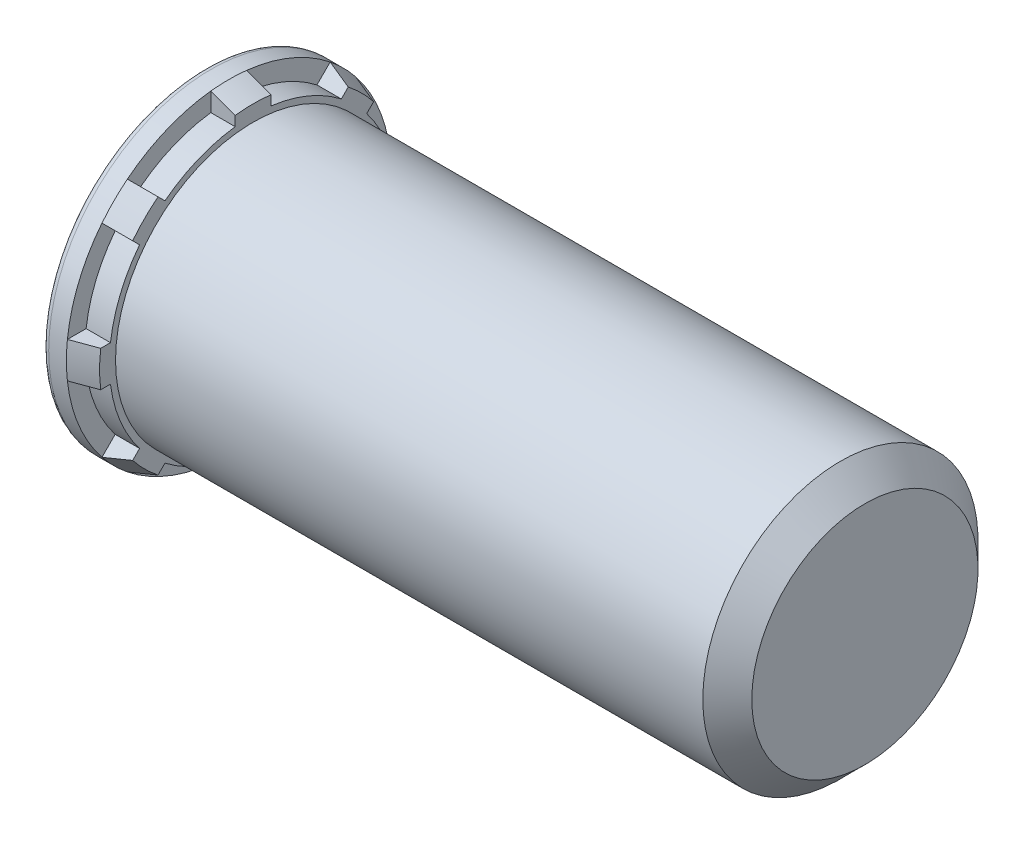
SolidWorks part; units mm, degrees
revolve "BaseBody" add sketch "BodySke" angle 360 about L6
sketch "BodySke" plane through (0, 0, 0) normal (0, 0, 1) x (1, 0, 0)
  line L0 (-0.4425, 2.8295) -> (-0.4425, 0)
  line L1 (0.4425, 2.7889) -> (0.4425, 2.5)
  line L2 (0, 2.95) -> (0.4425, 2.7889)
  line L3 (0.4425, 2.5) -> (11.1125, 2.5)
  line L4 (11.5575, 2.055) -> (11.5575, 0)
  line L5 (11.5575, 0) -> (-0.4425, 0)
  line L6 (0, 0) -> (50.554, 0) construction
  line L7 (-0.4425, 2.8295) -> (-0.44, 2.8295)
  line L8 (11.5575, 2.055) -> (11.1125, 2.5)
  line L9 (-0.322, 2.95) -> (0, 2.95)
  line L11 (0.8, 19.05) -> (0.8, -3.175) construction
  line L13 (-0.44, 2.8295) -> (-0.44, 2.832)
  arc A0 (-0.44, 2.832) -> (-0.322, 2.95) centre (-0.322, 2.832) cw
  dimension "Fillet_rad" = 0.118
  dimension "Body_ch_ang" = 45
  dimension "Minor_dia" = 4.11
  dimension "Diameter" = 5
  dimension "H_dia" = 5.9
  dimension "Advance" = 0.8
  dimension "D1" = 20
  dimension "Length" = 12
  dimension "D2" = 0.0025
  dimension "D3" = 0.0025
  dimension "Clinch_ht" = 0.4425
  dimension "Head_ht" = 0.885
cosmetic thread "ThreadCosmetic" [suppressed] parameters "Thread_length"=9.3, "Thread_minor"=4.11
ref_plane "Plane1" through (0, 0, 0) normal (0, 0, 1) x (1, 0, 0)
ref_plane "Plane2" through (0, 0, 0) normal (0, 1, 0) x (1, 0, 0)
ref_plane "Plane3" through (0, 0, 0) normal (1, 0, 0) x (0, 0, -1)
sketch "ThdSchSke" plane through (0, 0, 0) normal (0, 0, 1) x (1, 0, 0)
  line L0 (2.2575, -2.055) -> (1.9459, -2.5)
  line L1 (2.2575, -2.055) -> (2.5691, -2.5)
  line L2 (2.5691, -2.5) -> (2.5691, -3.125)
  line L3 (-3.175, 0) -> (5.1513, 0) construction
  line L5 (2.5691, -3.125) -> (1.9459, -3.125)
  line L6 (1.9459, -3.125) -> (1.9459, -2.5)
  line L7 (-0.4425, 2.8295) -> (-0.4425, -2.8295) construction
  dimension "Diameter" = 5
  dimension "Thread_minor" = 4.11
  dimension "Start" = 2.7
revolve "ThreadSchematic" [suppressed] cut sketch "ThdSchSke" angle 360 about L3
pattern_linear "ThdSchPat" [suppressed]
sketch "RibCutSke" plane through (0.4425, 1.7944, -0.091) normal (1, 0, 0) x (0, 0, -1)
  line L0 (0.2354, 0.7976) -> (0.2354, 1.1375)
  line L1 (1.5112, 0.2692) -> (1.7515, 0.5095)
  line L2 (0.2354, 0.6842) -> (0.2354, 0.0891) construction
  line L3 (-0.091, -1.7944) -> (-0.091, 5.0239) construction
  line L4 (-0.091, -1.7944) -> (0.2354, 0.6842) construction
  line L5 (-0.091, -1.7944) -> (1.431, 0.189) construction
  line L6 (1.431, 0.189) -> (1.0152, -0.2268) construction
  arc A1 (1.5112, 0.2692) -> (0.2354, 0.7976) centre (-0.091, -1.7944) ccw
  arc A2 (1.7515, 0.5095) -> (0.2354, 1.1375) centre (-0.091, -1.7944) ccw
  circle A3 centre (-0.091, -1.7944) radius 2.7889 construction
  circle A4 centre (-0.091, -1.7944) radius 2.5 construction
  dimension "Rib_root_half_angle" = 7.5
  dimension "Rib_root_gap_angle" = 30
  dimension "Angle" = 45
extrude "RibCut" cut sketch "RibCutSke" against normal blind 0.4425
pattern_circular "RibCutsPat" count 8 every 45 about axis through (0, 0, 0) along (1, 0, 0) of "RibCut"
equation "' \"Length@BodySke\" = 12"
equation "' \"H_dia@BodySke\" = 5.9"
equation "' \"Start@ThdSchSke\" = 2.7"
equation "' \"Diameter@BodySke\" = 5"
equation "' \"Minor_dia@BodySke\" = 4.11"
equation "' \"Advance@BodySke\" = 0.8"
equation "\"Fillet_rad@BodySke\" =   \"H_dia@BodySke\" *0.02"
equation "\"Clinch_ht@BodySke\" = \"H_dia@BodySke\" * 0.075"
equation "\"Head_ht@BodySke\" =  \"H_dia@BodySke\" * 0.15"
equation "\"Num_ribs@RibCutsPat\" = 8"
equation "\"Angle@RibCutSke\" =\"Angle@RibCutsPat\""
equation "\"Rib_root_half_angle@RibCutSke\" = \"Angle@RibCutSke\" / 6"
equation "\"Rib_root_gap_angle@RibCutSke\" = \"Angle@RibCutSke\" - (2 * \"Rib_root_half_angle@RibCutSke\" )"
equation "\"Rib_root_dia@RibCutSke\" = \"Diameter@BodySke\""
equation "\"Inner_dia@RibCutSke\" = \"Diameter@BodySke\" + ( \"H_dia@BodySke\" - \"Diameter@BodySke\" ) / 4"
equation "\"Outer_dia@RibCutSke\" = \"H_dia@BodySke\""
equation "\"Depth@RibCut\" = \"Clinch_ht@BodySke\""
equation "\"Thread_length@ThreadCosmetic\" = \"Length@BodySke\" - \"Start@ThdSchSke\""
equation "\"Thread_minor@ThreadCosmetic\" = \"Minor_dia@BodySke\""
equation "\"Thread_minor@ThdSchSke\" = \"Minor_dia@BodySke\""
equation "\"Diameter@ThdSchSke\" = \"Diameter@BodySke\""
equation "\"Overcut@ThdSchSke\" = \"Diameter@BodySke\" * 1.25"
equation "\"Num_threads@ThdSchPat\" = int( \"Thread_length@ThreadCosmetic\" / \"Advance@BodySke\" + 0.999 )  + 1"
equation "\"Advance@ThdSchPat\" = \"Thread_length@ThreadCosmetic\" /  (\"Num_threads@ThdSchPat\" - 1) 'relax it"
equation "\"Num_threads@ThdSchPat\" = \"Num_threads@ThdSchPat\" - sgn( \"Num_threads@ThdSchPat\" - 1) '---chamfered tips only---"
